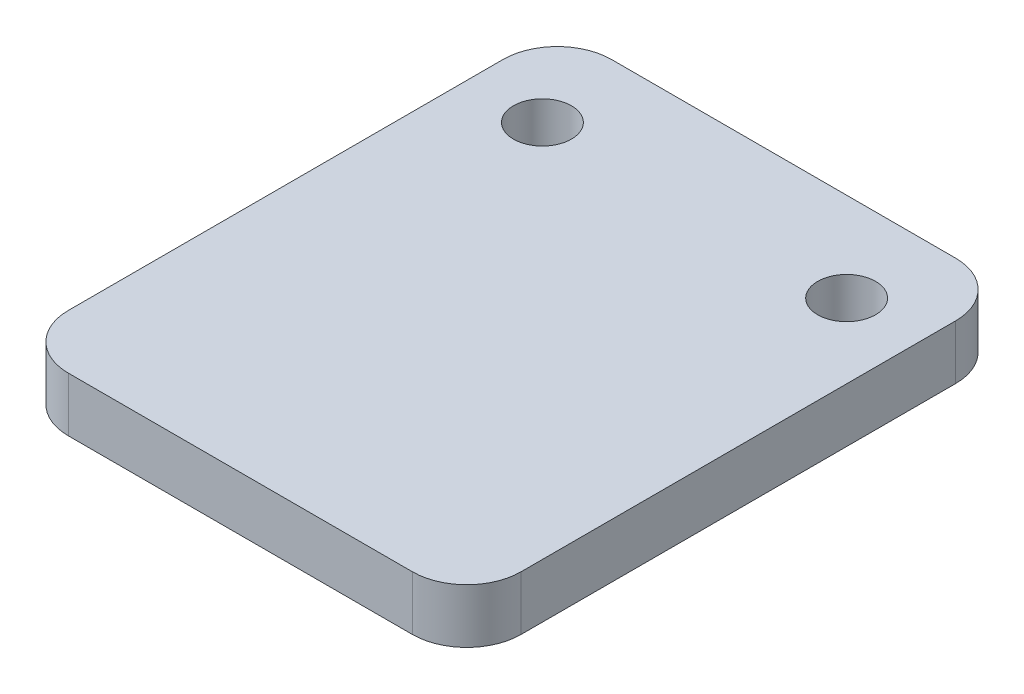
SolidWorks part; units mm, degrees
ref_plane "Front Plane" through (0, 0, 0) normal (0, 0, 1) x (1, 0, 0)
ref_plane "Top Plane" through (0, 0, 0) normal (0, 1, 0) x (1, 0, 0)
ref_plane "Right Plane" through (0, 0, 0) normal (1, 0, 0) x (0, 0, -1)
sketch "Sketch1" plane through (0, 0, 0) normal (0, 1, 0) x (1, 0, 0)
  line L0 (0, 0) -> (0, 15) construction
  line L1 (12.5, -15) -> (-12.5, -15)
  line L2 (12.5, -15) -> (12.5, 15)
  line L3 (12.5, 15) -> (-12.5, 15)
  line L4 (-12.5, -15) -> (-12.5, 15)
  line L5 (12.5, -15) -> (-12.5, 15) construction
  line L6 (12.5, 15) -> (-12.5, -15) construction
  circle A0 centre (-8.4, 10.08) radius 1.6
  circle A1 centre (8.4, 10.08) radius 1.6
  point P1 (0, 0)
  dimension "D3" = 3.2
  dimension "D1" = 25
  dimension "D2" = 30
  dimension "D4" = 8.4
extrude "Boss-Extrude1" add sketch "Sketch1" along normal mid plane 3
fillet "Fillet1" radius 3 4 edges at (-12.5, 0, -15) (12.5, 0, -15) (-12.5, 0, 15) (12.5, 0, 15)
